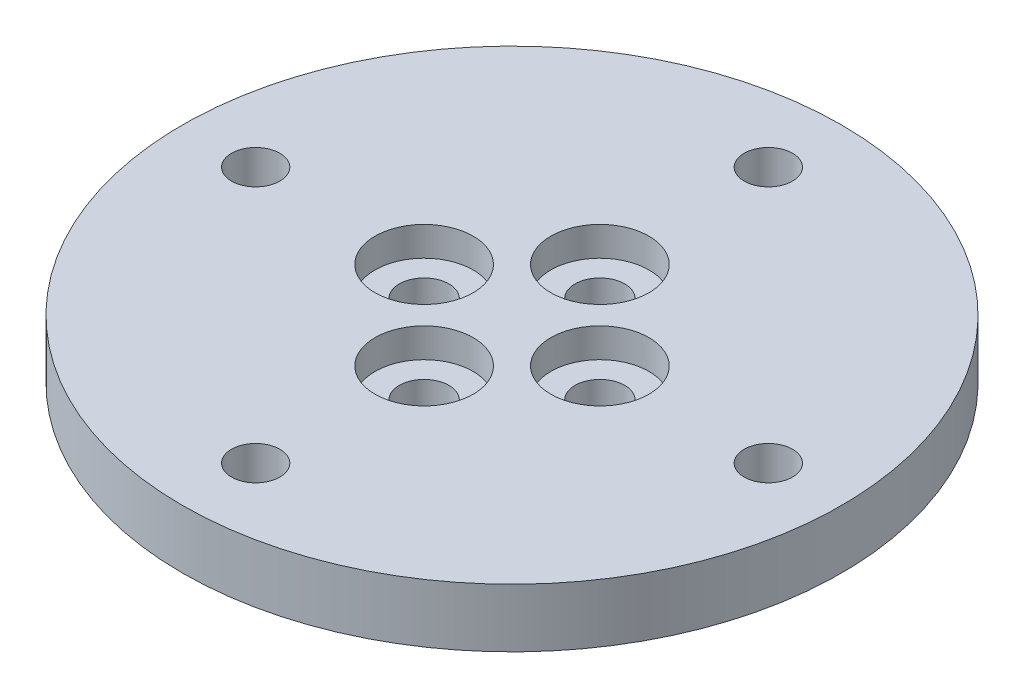
SolidWorks part; units mm, degrees
ref_plane "Спереди" through (0, 0, 0) normal (0, 0, 1) x (1, 0, 0)
ref_plane "Сверху" through (0, 0, 0) normal (0, 1, 0) x (1, 0, 0)
ref_plane "Справа" through (0, 0, 0) normal (1, 0, 0) x (0, 0, -1)
sketch "Эскиз1" plane through (0, 0, 0) normal (0, 1, 0) x (1, 0, 0)
  line L0 (0, 22.5) -> (0, -22.5) construction
  line L1 (22.5, 0) -> (-22.5, 0) construction
  circle A0 centre (0, 0) radius 22.5
  dimension "D1" = 45
extrude "Бобышка-Вытянуть1" add sketch "Эскиз1" along normal blind 4
sketch "Эскиз2" plane through (0, 4, 0) normal (0, 1, 0) x (1, 0, 0)
  circle A0 centre (0, 0) radius 6 construction
  circle A1 centre (0, 0) radius 17.5 construction
  dimension "D1" = 12
  dimension "D2" = 35
hole_wizard "Цековка для  винта с полукруглой головкой M31" positions "Эскиз4" profile "Эскиз5" counterbore size "M3" standard "Ansi Metric" end condition through all
sketch "Эскиз4" plane through (0, 4, 0) normal (0, 1, 0) x (1, 0, 0)
  line L0 (0, 22.5) -> (0, -22.5) construction
  line L1 (22.5, 0) -> (-22.5, 0) construction
  circle A0 centre (0, 0) radius 6 construction
  point P0 (0, 6)
  point P6 (-6, 0)
  point P10 (0, -6)
  point P12 (6, 0)
sketch "Эскиз5" plane through (0, 4, -6) normal (1, 0, 0) x (0, 0, 1)
  line L0 (0, 0) -> (0, 4)
  line L1 (0, 4) -> (1.7, 4)
  line L3 (1.7, 4) -> (1.7, 2)
  line L4 (1.7, 2) -> (3.35, 2)
  line L5 (3.35, 2) -> (3.35, 0)
  line L7 (3.35, 0) -> (0, 0)
  line L11 (0, -6.35) -> (0, 107.95) construction
  dimension "Диаметр сквозного отверстия" = 3.4
  dimension "Глубина сквозного отверстия" = 4
  dimension "Диаметр цековки" = 6.7
  dimension "Глубина цековки" = 2
hole_wizard "Отверстие обработанное метчиком M4x0.71" positions "Эскиз7" profile "Эскиз6" tap size "M4x0.7" standard "Ansi Metric" end condition through all
sketch "Эскиз7" plane through (0, 4, 0) normal (0, 1, 0) x (1, 0, 0)
  line L0 (22.5, 0) -> (-22.5, 0) construction
  line L1 (0, 22.5) -> (0, -22.5) construction
  circle A0 centre (0, 0) radius 17.5 construction
  point P0 (-17.5, 0)
  point P6 (0, -17.5)
  point P10 (17.5, 0)
  point P12 (0, 17.5)
sketch "Эскиз6" plane through (-17.5, 4, 0) normal (1, 0, 0) x (0, 0, 1)
  line L0 (0, 0) -> (0, 4)
  line L1 (0, 4) -> (1.65, 4)
  line L2 (1.65, 4) -> (1.65, 0)
  line L5 (1.65, 0) -> (0, 0)
  line L11 (0, -6.35) -> (0, 107.95) construction
  dimension "Диаметр проходного сверла" = 3.3
  dimension "Глубина проходного сверла" = 4
cosmetic thread "Отверстие резьбы1" parameters "D2"=4
cosmetic thread "Отверстие резьбы2" parameters "D2"=4
cosmetic thread "Отверстие резьбы3" parameters "D2"=4
cosmetic thread "Отверстие резьбы4" parameters "D2"=4
